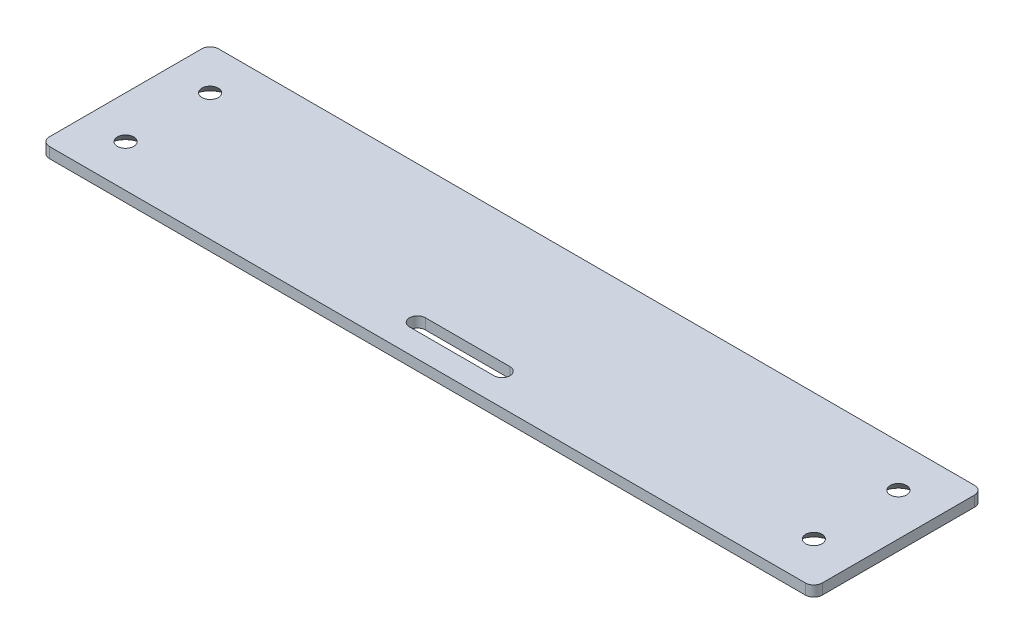
SolidWorks part; units mm, degrees
material "1060 Alloy"
ref_plane "Front Plane" through (0, 0, 0) normal (0, 0, 1) x (1, 0, 0)
ref_plane "Top Plane" through (0, 0, 0) normal (0, 1, 0) x (1, 0, 0)
ref_plane "Right Plane" through (0, 0, 0) normal (1, 0, 0) x (0, 0, -1)
sketch "Sketch1" plane through (0, 0, 0) normal (0, 1, 0) x (1, 0, 0)
  line L0 (34.8254, -125.5048) -> (-192.2255, -125.5048)
  line L1 (-194.7655, -232.1944) -> (-194.7655, 428.2056) construction
  line L3 (-194.7655, -128.0448) -> (-194.7655, -173.7648)
  line L5 (37.0095, -232.1944) -> (37.0095, 428.2056) construction
  line L6 (37.3654, -173.7648) -> (37.3654, -128.0448)
  line L9 (-192.2255, -176.3048) -> (34.8254, -176.3048)
  arc A2 (34.8254, -125.5048) -> (37.3654, -128.0448) centre (34.8254, -128.0448) cw
  arc A3 (34.8254, -176.3048) -> (37.3654, -173.7648) centre (34.8254, -173.7648) ccw
  arc A4 (-194.7655, -173.7648) -> (-192.2255, -176.3048) centre (-192.2255, -173.7648) ccw
  arc A5 (-194.7655, -128.0448) -> (-192.2255, -125.5048) centre (-192.2255, -128.0448) cw
  point P6 (-194.7655, -176.3048)
  point P13 (-194.7655, -125.5048)
  point P20 (37.0095, -125.5048)
  point P23 (37.0095, -176.3048)
  dimension "D1" = 2.54
  dimension "D2" = 2.54
  dimension "D3" = 2.54
  dimension "D4" = 2.54
extrude "Boss-Extrude1" add sketch "Sketch1" along normal blind 3.175
sketch "Sketch2" plane through (0, 0, 0) normal (0, -1, 0) x (1, 0, 0)
  line L0 (-182.0655, 150.9048) -> (-194.7655, 150.9048)
  line L2 (-182.0655, 150.9048) -> (-182.0655, 163.6048)
  line L3 (-182.0655, 150.9048) -> (-182.0655, 138.2048)
  line L4 (37.3654, 150.9048) -> (24.6654, 150.9048)
  line L5 (37.3654, 173.7648) -> (37.3654, 128.0448) construction
  line L6 (24.6654, 150.9048) -> (24.6654, 163.6048)
  line L7 (24.6654, 150.9048) -> (24.6654, 138.2048)
  line L8 (-194.7655, 128.0448) -> (-194.7655, 173.7648) construction
hole_wizard "#10 (0.1935) Diameter Hole1" positions "Sketch3" profile "Sketch4" hole size "#10" standard "ANSI Inch" end condition through all
sketch "Sketch3" plane through (0, 0, 0) normal (0, -1, 0) x (-1, 0, 0)
  point P0 (-24.6654, -163.6048)
  point P3 (-24.6654, -138.2048)
  point P6 (182.0655, -138.2048)
  point P9 (182.0655, -163.6048)
sketch "Sketch4" plane through (24.6654, 0, 163.6048) normal (1, 0, 0) x (0, 0, -1)
  line L0 (0, 0) -> (0, 3.175)
  line L1 (0, 3.175) -> (2.4574, 3.175)
  line L2 (2.4574, 3.175) -> (2.4574, 3.1776)
  line L3 (2.4574, 3.1776) -> (5.2197, 0)
  line L5 (5.2197, 0) -> (0, 0)
  line L6 (-2.4575, 3.1776) -> (-5.2197, 0) construction
  line L11 (0, -6.35) -> (0, 107.95) construction
  dimension "Thru Hole Dia." = 4.9149
  dimension "Thru Hole Depth" = 3.175
  dimension "Near C'Sink Dia." = 10.4394
  dimension "Near C'Sink Angle" = 82
sketch "Sketch6" plane through (0, 0, 0) normal (0, -1, 0) x (1, 0, 0)
  line L0 (-78.7001, 166.7798) -> (-78.7001, 176.3048) construction
  line L2 (-192.2255, 176.3048) -> (34.8254, 176.3048) construction
  line L3 (-66.178, 166.7798) -> (-91.2221, 166.7798) construction
  line L4 (-65.8221, 169.1674) -> (-91.2221, 169.1674)
  line L5 (-91.2221, 164.3922) -> (-65.8221, 164.3922)
  arc A0 (-91.2221, 169.1674) -> (-91.2221, 164.3922) centre (-91.2221, 166.7798) ccw
  arc A1 (-65.8221, 169.1674) -> (-65.8221, 164.3922) centre (-65.8221, 166.7798) cw
extrude "Cut-Extrude1" cut sketch "Sketch6" against normal blind 3.175
